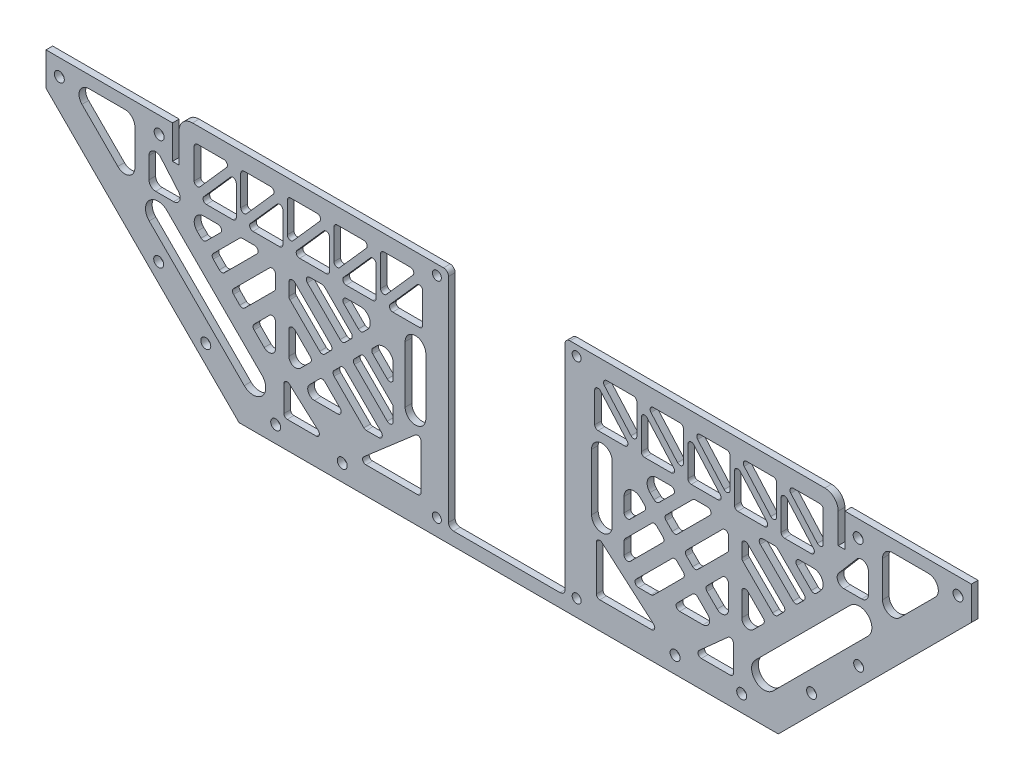
SolidWorks part; units mm, degrees
material "Thornel Mat VMA"
ref_plane "前视基准面" through (0, 0, 0) normal (0, 0, 1) x (1, 0, 0)
ref_plane "上视基准面" through (0, 0, 0) normal (0, 1, 0) x (1, 0, 0)
ref_plane "右视基准面" through (0, 0, 0) normal (1, 0, 0) x (0, 0, -1)
sketch "草图1" plane through (0, 0, 0) normal (0, 0, 1) x (1, 0, 0)
  line L0 (-101, 30) -> (-101, 0)
  line L1 (-101, 0) -> (101, 0)
  line L2 (101, 0) -> (101, 30)
  line L3 (-101, 30) -> (-139, 30)
  line L5 (-81, -58) -> (81, -58)
  line L7 (139, 30) -> (101, 30)
  line L8 (0, 0) -> (0, -58) construction
  line L9 (-135, 25) -> (-105, 25) construction
  line L10 (-135, 25) -> (-135, 5) construction
  line L11 (-135, 5) -> (-105, 5) construction
  line L12 (-105, 25) -> (-105, 5) construction
  line L13 (105, 25) -> (105, 5) construction
  line L14 (135, 5) -> (105, 5) construction
  line L15 (135, 25) -> (135, 5) construction
  line L16 (135, 25) -> (105, 25) construction
  line L17 (-70, -53) -> (-50, -53) construction
  line L18 (70, -53) -> (50, -53) construction
  line L19 (-139, 30) -> (-139, 0)
  line L20 (-139, 0) -> (-81, -58)
  line L21 (81, -58) -> (139, 0)
  line L22 (139, 0) -> (139, 30)
  circle A0 centre (-135, 25) radius 1.5
  circle A1 centre (-105, 25) radius 1.5
  circle A2 centre (-105, 5) radius 1.5
  circle A3 centre (-135, 5) radius 1.5
  circle A4 centre (135, 5) radius 1.5
  circle A5 centre (105, 5) radius 1.5
  circle A6 centre (105, 25) radius 1.5
  circle A7 centre (135, 25) radius 1.5
  circle A8 centre (-70, -53) radius 1.5
  circle A9 centre (-50, -53) radius 1.5
  circle A10 centre (50, -53) radius 1.5
  circle A11 centre (70, -53) radius 1.5
  point P4 (0, 0)
  dimension "D5" = 3
  dimension "D10" = 3
  dimension "D1" = 30
  dimension "D2" = 202
  dimension "D3" = 58
  dimension "D4" = 38
  dimension "D6" = 5
  dimension "D7" = 5
  dimension "D8" = 4
  dimension "D9" = 4
  dimension "D11" = 20
  dimension "D12" = 50
  dimension "D13" = 5
  dimension "D14" = 45
extrude "凸台-拉伸1" add sketch "草图1" along normal blind 2
sketch "草图2" plane through (0, 0, 2) normal (0, 0, 1) x (1, 0, 0)
  line L0 (-105.1421, -28.201) -> (-91, -42.3431) construction
  line L1 (0, 0) -> (0, -58) construction
  line L2 (-81, -58) -> (81, -58) construction
  line L3 (-139, 0) -> (-81, -58) construction
  line L4 (105.1421, -28.201) -> (91, -42.3431) construction
  circle A0 centre (-105.1421, -28.201) radius 1.5
  circle A1 centre (-91, -42.3431) radius 1.5
  circle A2 centre (91, -42.3431) radius 1.5
  circle A3 centre (105.1421, -28.201) radius 1.5
  dimension "D3" = 3
  dimension "D1" = 4
  dimension "D2" = 20
  dimension "D4" = 10
extrude "切除-拉伸1" cut sketch "草图2" against normal through all
sketch "草图3" plane through (0, 0, 2) normal (0, 0, 1) x (1, 0, 0)
  line L0 (139, 0) -> (139, 30) construction
  line L1 (-139, 30) -> (139, 30)
  line L2 (-139, 30) -> (-139, 10)
  line L3 (-139, 10) -> (139, 10)
  line L4 (139, 30) -> (139, 10)
  circle A0 centre (135, 5) radius 1.5 construction
  dimension "D1" = 5
extrude "切除-拉伸2" cut sketch "草图3" against normal through all
sketch "草图4" plane through (0, 0, 2) normal (0, 0, 1) x (1, 0, 0)
  line L0 (0, 0) -> (0, -58) construction
  line L1 (-81, -58) -> (81, -58) construction
  line L2 (-99, 0) -> (-99, 9)
  line L3 (101, 0) -> (-101, 0) construction
  line L4 (-95, 13) -> (95, 13)
  line L5 (0, 13) -> (0, 0)
  line L6 (-101, 0) -> (-101, 10) construction
  line L7 (-99, 0) -> (99, 0)
  line L8 (99, 0) -> (99, 9)
  arc A0 (-95, 13) -> (-99, 9) centre (-95, 9) ccw
  arc A1 (95, 13) -> (99, 9) centre (95, 9) cw
  line M15 (101, 0) -> (-101, 0)
  dimension "D3" = 4
  dimension "D1" = 2
  dimension "D2" = 13
extrude "凸台-拉伸2" add sketch "草图4" against normal up to surface (2 mm away) contours L4 A0 L2 L5 M15 | A1 L4 L5 L8 M15 up to face at (-103.6421, -28.201, 0)
sketch "草图8" plane through (0, 0, 2) normal (0, 0, 1) x (1, 0, 0)
  line L0 (-18.0726, -54) -> (16.9274, -54)
  line L1 (16.9274, -54) -> (16.9274, 16.3442)
  line L2 (16.9274, 16.3442) -> (-18.0726, 16.3442)
  line L3 (-18.0726, 16.3442) -> (-18.0726, -54)
  line L4 (-81, -58) -> (81, -58) construction
  line L48 (14.9274, 12.8) -> (14.9274, -43)
  line L49 (14.9274, -43) -> (13.9274, -43)
  line L50 (13.9274, -43) -> (13.9274, -31)
  line L51 (13.9274, -31) -> (11.9274, -31)
  line L52 (11.9274, -31) -> (11.9274, -43)
  line L53 (11.9274, -43) -> (10.9274, -43)
  line L54 (10.9274, -43) -> (10.9274, -31)
  line L55 (10.9274, -31) -> (8.9274, -31)
  line L56 (8.9274, -31) -> (8.9274, -43)
  line L57 (8.9274, -43) -> (7.9274, -43)
  line L58 (7.9274, -43) -> (7.9274, 12.8)
  line L59 (7.9274, 12.8) -> (5.9274, 12.8)
  line L60 (5.9274, 12.8) -> (5.9274, -43)
  line L61 (5.9274, -43) -> (4.9274, -43)
  line L62 (4.9274, -43) -> (4.9274, 12.8)
  line L63 (4.9274, 12.8) -> (2.9274, 12.8)
  line L64 (2.9274, 12.8) -> (2.9274, -43)
  line L65 (2.9274, -43) -> (1.9274, -43)
  line L66 (1.9274, -43) -> (1.9274, 12.8)
  line L67 (1.9274, 12.8) -> (-0.0726, 12.8)
  line L68 (-0.0726, 12.8) -> (-0.0726, -43)
  line L69 (-0.0726, -43) -> (-1.0726, -43)
  line L70 (-1.0726, -43) -> (-1.0726, 12.8)
  line L71 (-1.0726, 12.8) -> (-3.0726, 12.8)
  line L72 (-3.0726, 12.8) -> (-3.0726, -43)
  line L73 (-3.0726, -43) -> (-4.0726, -43)
  line L74 (-4.0726, -43) -> (-4.0726, 12.8)
  line L75 (-4.0726, 12.8) -> (-6.0726, 12.8)
  line L76 (-6.0726, 12.8) -> (-6.0726, -43)
  line L77 (-6.0726, -43) -> (-7.0726, -43)
  line L78 (-7.0726, -43) -> (-7.0726, 12.8)
  line L79 (-7.0726, 12.8) -> (-9.0726, 12.8)
  line L80 (-9.0726, 12.8) -> (-9.0726, -43)
  line L81 (-9.0726, -43) -> (-10.0726, -43)
  line L82 (-10.0726, -43) -> (-10.0726, 12.8)
  line L83 (-10.0726, 12.8) -> (-12.0726, 12.8)
  line L84 (-12.0726, 12.8) -> (-12.0726, -43)
  line L85 (-12.0726, -43) -> (-13.0726, -43)
  line L86 (-13.0726, -43) -> (-13.0726, 12.8)
  line L87 (-13.0726, 12.8) -> (-15.0726, 12.8)
  line L88 (-15.0726, 12.8) -> (-15.0726, -43)
  line L89 (-15.0726, -43) -> (-16.0726, -43)
  line L90 (-16.0726, -43) -> (-16.0726, 12.8)
  line L91 (-16.0726, 12.8) -> (-21.5726, 12.8)
  line L92 (-24.3726, 10) -> (-24.3726, -53)
  line L93 (-21.5726, -55.8) -> (20.4274, -55.8)
  line L94 (23.2274, -53) -> (23.2274, 10)
  line L95 (20.4274, 12.8) -> (14.9274, 12.8)
  line L96 (14.9274, 12.8) -> (14.9274, -43)
  line L97 (14.9274, -43) -> (13.9274, -43)
  line L98 (13.9274, -43) -> (13.9274, -31)
  line L99 (13.9274, -31) -> (11.9274, -31)
  line L100 (11.9274, -31) -> (11.9274, -43)
  line L101 (11.9274, -43) -> (10.9274, -43)
  line L102 (10.9274, -43) -> (10.9274, -31)
  line L103 (10.9274, -31) -> (8.9274, -31)
  line L104 (8.9274, -31) -> (8.9274, -43)
  line L105 (8.9274, -43) -> (7.9274, -43)
  line L106 (7.9274, -43) -> (7.9274, 12.8)
  line L107 (7.9274, 12.8) -> (5.9274, 12.8)
  line L108 (5.9274, 12.8) -> (5.9274, -43)
  line L109 (5.9274, -43) -> (4.9274, -43)
  line L110 (4.9274, -43) -> (4.9274, 12.8)
  line L111 (4.9274, 12.8) -> (2.9274, 12.8)
  line L112 (2.9274, 12.8) -> (2.9274, -43)
  line L113 (2.9274, -43) -> (1.9274, -43)
  line L114 (1.9274, -43) -> (1.9274, 12.8)
  line L115 (1.9274, 12.8) -> (-0.0726, 12.8)
  line L116 (-0.0726, 12.8) -> (-0.0726, -43)
  line L117 (-0.0726, -43) -> (-1.0726, -43)
  line L118 (-1.0726, -43) -> (-1.0726, 12.8)
  line L119 (-1.0726, 12.8) -> (-3.0726, 12.8)
  line L120 (-3.0726, 12.8) -> (-3.0726, -43)
  line L121 (-3.0726, -43) -> (-4.0726, -43)
  line L122 (-4.0726, -43) -> (-4.0726, 12.8)
  line L123 (-4.0726, 12.8) -> (-6.0726, 12.8)
  line L124 (-6.0726, 12.8) -> (-6.0726, -43)
  line L125 (-6.0726, -43) -> (-7.0726, -43)
  line L126 (-7.0726, -43) -> (-7.0726, 12.8)
  line L127 (-7.0726, 12.8) -> (-9.0726, 12.8)
  line L128 (-9.0726, 12.8) -> (-9.0726, -43)
  line L129 (-9.0726, -43) -> (-10.0726, -43)
  line L130 (-10.0726, -43) -> (-10.0726, 12.8)
  line L131 (-10.0726, 12.8) -> (-12.0726, 12.8)
  line L132 (-12.0726, 12.8) -> (-12.0726, -43)
  line L133 (-12.0726, -43) -> (-13.0726, -43)
  line L134 (-13.0726, -43) -> (-13.0726, 12.8)
  line L135 (-13.0726, 12.8) -> (-15.0726, 12.8)
  line L136 (-15.0726, 12.8) -> (-15.0726, -43)
  line L137 (-15.0726, -43) -> (-16.0726, -43)
  line L138 (-16.0726, -43) -> (-16.0726, 12.8)
  line L139 (-16.0726, 12.8) -> (-21.5726, 12.8)
  line L140 (-24.3726, 10) -> (-24.3726, -53)
  line L141 (-21.5726, -55.8) -> (20.4274, -55.8)
  line L142 (23.2274, -53) -> (23.2274, 10)
  line L143 (20.4274, 12.8) -> (14.9274, 12.8)
  circle A0 centre (20.4274, 10) radius 1.35 construction
  circle A1 centre (-21.5726, 10) radius 1.35 construction
  circle A2 centre (-21.5726, -53) radius 1.35 construction
  circle A3 centre (20.4274, -53) radius 1.35 construction
  arc A4 (-21.5726, 12.8) -> (-24.3726, 10) centre (-21.5726, 10) ccw
  arc A5 (-24.3726, -53) -> (-21.5726, -55.8) centre (-21.5726, -53) ccw
  arc A6 (20.4274, -55.8) -> (23.2274, -53) centre (20.4274, -53) ccw
  arc A7 (23.2274, 10) -> (20.4274, 12.8) centre (20.4274, 10) ccw
  arc A8 (-21.5726, 12.8) -> (-24.3726, 10) centre (-21.5726, 10) ccw
  arc A9 (-24.3726, -53) -> (-21.5726, -55.8) centre (-21.5726, -53) ccw
  arc A10 (20.4274, -55.8) -> (23.2274, -53) centre (20.4274, -53) ccw
  arc A11 (23.2274, 10) -> (20.4274, 12.8) centre (20.4274, 10) ccw
  circle A12 centre (20.4274, 10) radius 1.35
  circle A13 centre (-21.5726, 10) radius 1.35
  circle A14 centre (-21.5726, -53) radius 1.35
  circle A15 centre (20.4274, -53) radius 1.35
  line M64 (95, 13) -> (-95, 13)
  dimension "D2" = 2
  dimension "D3" = 2
  dimension "D4" = 4
  dimension "D1" = 0
extrude "切除-拉伸6" cut sketch "草图8" against normal blind 10 contours L1 L143 L96 L97 L98 L99 L100 L101 L102 L103 L104 L105 L106 L107 L108 L109 L110 L111 L112 L113 L114 L115 L116 L117 L118 L119 L120 L121 L122 L123 L124 L125 L126 L127 L128 L129 L130 L131 L132 L133 L134 L135 L136 L137 L138 L139 L3 L0 | L143 L1 L3 L139 L138 L137 L136 L135 L134 L133 L132 L131 L130 L129 L128 L127 L126 L125 L124 L123 L122 L121 L120 L119 L118 L117 L116 L115 L114 L113 L112 L111 L110 L109 L108 L107 L106 L105 L104 L103 L102 L101 L100 L99 L98 L97 L96 M64 | L2 L3 L1 M64 | A14 | A15 | A12 | A13
fillet "圆角2" radius 1.5 4 edges at (16.9274, 13, 1) (-18.0726, 13, 1) (16.9274, -54, 1) (-18.0726, -54, 1)
sketch "草图9" plane through (0, 0, 2) normal (0, 0, 1) x (1, 0, 0)
  line L0 (-105.327, -16.3413) -> (-76.7637, -44.9046) construction
  line L3 (-102.6508, -13.6651) -> (-74.0875, -42.2284)
  line L6 (-108.0031, -19.0174) -> (-79.4398, -47.5807)
  line L9 (-139, 0) -> (-81, -58) construction
  line L10 (-80.0246, -9.5495) -> (-76.3296, -9.5495)
  line L11 (-126.0803, 6.3467) -> (-115.3054, 6.3467)
  line L12 (-112.3054, 3.3467) -> (-112.3054, -7.4282)
  line L13 (-117.4268, -9.5495) -> (-128.2017, 1.2254)
  line L14 (-104.5409, -0.7265) -> (-99.1595, -7.0389)
  line L15 (-100.6815, -10.3364) -> (-106.0629, -10.3364)
  line L16 (-108.0629, -8.3364) -> (-108.0629, -2.024)
  line L17 (-91.583, -9.5495) -> (-87.3282, -9.5495)
  line L18 (-70.033, -13.8917) -> (-70.033, -17.6295)
  line L19 (-73.4472, -34.6588) -> (-76.4836, -31.6224)
  line L20 (-80.7738, -9.8598) -> (-88.7608, -17.8469)
  line L21 (-75.5804, -11.3582) -> (-85.4149, -21.1927)
  line L22 (-71.8417, -13.1425) -> (-82.6535, -23.9542)
  line L23 (-86.579, -11.3582) -> (-90.9142, -15.6935)
  line L24 (-70.3434, -18.3787) -> (-79.2862, -27.3215)
  line L25 (-86.9133, -21.1927) -> (-88.7608, -19.3452)
  line L26 (-80.7846, -27.3215) -> (-82.6535, -25.4526)
  line L27 (-70.033, -26.2313) -> (-70.033, -33.2446)
  line L28 (0, -58) -> (0, 0) construction
  line L29 (-71.8417, -25.4821) -> (-76.4836, -30.1241)
  line L30 (-92.4126, -15.6935) -> (-93.6255, -14.4805)
  line L31 (-81, -58) -> (81, -58) construction
  line L32 (-18.0726, -20.5) -> (0, -20.5) construction
  line L33 (-18.0726, 11.5) -> (-18.0726, -52.5) construction
  line L44 (-48.229, -20.269) -> (-46.8148, -21.6832) construction
  line L49 (-70.033, -15.7606) -> (-68.033, -15.7606) construction
  line L50 (-68.033, -15.7606) -> (-68.033, -17.2319) construction
  line L51 (-43.6535, -15.6935) -> (-42.4405, -14.4805)
  line L52 (-49.4871, -11.3582) -> (-45.1518, -15.6935)
  line L53 (-44.483, -9.5495) -> (-48.7379, -9.5495)
  line L54 (-56.0414, -9.5495) -> (-59.7365, -9.5495)
  line L55 (-60.4856, -11.3582) -> (-50.6511, -21.1927)
  line L56 (-49.1527, -21.1927) -> (-47.3052, -19.3452)
  line L57 (-55.2922, -9.8598) -> (-47.3052, -17.8469)
  line L58 (-66.033, -13.8917) -> (-66.033, -17.6295)
  line L59 (-65.7227, -18.3787) -> (-56.7799, -27.3215)
  line L60 (-55.2815, -27.3215) -> (-53.4126, -25.4526)
  line L61 (-64.2243, -13.1425) -> (-53.4126, -23.9542)
  line L62 (-66.033, -26.2313) -> (-66.033, -33.2446)
  line L63 (-64.2243, -25.4821) -> (-59.5824, -30.1241)
  line L64 (-62.6188, -34.6588) -> (-59.5824, -31.6224)
  line L65 (-46.8148, -21.6832) -> (-45.4006, -20.269) construction
  line L66 (-34.6811, -19.3514) -> (-34.6811, -23.6063)
  line L67 (-36.4898, -24.3555) -> (-40.825, -20.0203)
  line L68 (-40.825, -18.5219) -> (-39.6121, -17.309)
  line L69 (-34.9914, -30.1607) -> (-42.9784, -22.1737)
  line L70 (-46.3243, -24.0212) -> (-44.4768, -22.1737)
  line L71 (-36.4898, -35.3541) -> (-46.3243, -25.5195)
  line L72 (-34.6811, -30.9099) -> (-34.6811, -34.6049)
  line L73 (-38.274, -39.0928) -> (-49.0858, -28.281)
  line L74 (-52.4531, -30.1499) -> (-50.5842, -28.281)
  line L75 (-43.5102, -40.5911) -> (-52.4531, -31.6483)
  line L76 (-39.0232, -40.9015) -> (-42.7611, -40.9015)
  line L77 (-51.3629, -40.9015) -> (-58.3762, -40.9015)
  line L78 (-50.6137, -39.0928) -> (-55.2556, -34.4509)
  line L79 (-59.7904, -37.4873) -> (-56.754, -34.4509)
  line L80 (-65.8616, -40.396) -> (-57.2022, -48.1573)
  line L81 (-57.8696, -49.9019) -> (-66.529, -49.9019)
  line L82 (-67.529, -48.9019) -> (-67.529, -41.1406)
  line L83 (-28.002, -34.6782) -> (-43.5483, -48.1461)
  line L84 (-42.8936, -49.9019) -> (-27.3472, -49.9019)
  line L85 (-26.3472, -48.9019) -> (-26.3472, -35.434)
  line L86 (-28.002, -11.9698) -> (-28.002, -29.0302) construction
  line L87 (-24.8989, -11.9698) -> (-24.8989, -29.0302)
  line L88 (-31.105, -11.9698) -> (-31.105, -29.0302)
  line L100 (-94.4948, 7.1872) -> (-94.4948, -1.8511)
  line L102 (-85.5038, 8.1872) -> (-93.4948, 8.1872)
  line L103 (-90.831, -6.1261) -> (-82.8401, -6.1261)
  line L104 (-81.8401, -5.1261) -> (-81.8401, 3.9122)
  line L105 (-80.4948, 7.1872) -> (-80.4948, -1.8511)
  line L106 (-84.7546, 6.5248) -> (-92.7456, -2.5135)
  line L107 (-83.5893, 4.5745) -> (-91.5802, -4.4637)
  line L108 (-70.7546, 6.5248) -> (-78.7456, -2.5135)
  line L109 (-71.5038, 8.1872) -> (-79.4948, 8.1872)
  line L110 (-76.831, -6.1261) -> (-68.8401, -6.1261)
  line L111 (-67.8401, -5.1261) -> (-67.8401, 3.9122)
  line L112 (-69.5893, 4.5745) -> (-77.5802, -4.4637)
  line L113 (-66.4948, 7.1872) -> (-66.4948, -1.8511)
  line L114 (-56.7546, 6.5248) -> (-64.7456, -2.5135)
  line L115 (-57.5038, 8.1872) -> (-65.4948, 8.1872)
  line L116 (-62.831, -6.1261) -> (-54.8401, -6.1261)
  line L117 (-53.8401, -5.1261) -> (-53.8401, 3.9122)
  line L118 (-55.5893, 4.5745) -> (-63.5802, -4.4637)
  line L119 (-52.4948, 7.1872) -> (-52.4948, -1.8511)
  line L120 (-42.7546, 6.5248) -> (-50.7456, -2.5135)
  line L121 (-43.5038, 8.1872) -> (-51.4948, 8.1872)
  line L122 (-48.831, -6.1261) -> (-40.8401, -6.1261)
  line L123 (-39.8401, -5.1261) -> (-39.8401, 3.9122)
  line L124 (-41.5893, 4.5745) -> (-49.5802, -4.4637)
  line L125 (-38.4948, 7.1872) -> (-38.4948, -1.8511)
  line L126 (-28.7546, 6.5248) -> (-36.7456, -2.5135)
  line L127 (-29.5038, 8.1872) -> (-37.4948, 8.1872)
  line L128 (-34.831, -6.1261) -> (-26.8401, -6.1261)
  line L129 (-25.8401, -5.1261) -> (-25.8401, 3.9122)
  line L130 (-27.5893, 4.5745) -> (-35.5802, -4.4637)
  arc A6 (-102.6508, -13.6651) -> (-108.0031, -19.0174) centre (-105.327, -16.3413) ccw
  arc A7 (-79.4398, -47.5807) -> (-74.0875, -42.2284) centre (-76.7637, -44.9046) ccw
  arc A8 (-112.3054, -7.4282) -> (-117.4268, -9.5495) centre (-115.3054, -7.4282) cw
  arc A9 (-112.3054, 3.3467) -> (-115.3054, 6.3467) centre (-115.3054, 3.3467) ccw
  arc A10 (-126.0803, 6.3467) -> (-128.2017, 1.2254) centre (-126.0803, 3.3467) ccw
  arc A11 (-100.6815, -10.3364) -> (-99.1595, -7.0389) centre (-100.6815, -8.3364) ccw
  arc A12 (-106.0629, -10.3364) -> (-108.0629, -8.3364) centre (-106.0629, -8.3364) cw
  arc A13 (-104.5409, -0.7265) -> (-108.0629, -2.024) centre (-106.0629, -2.024) ccw
  arc A14 (-70.033, -33.2446) -> (-73.4472, -34.6588) centre (-72.033, -33.2446) cw
  arc A16 (-91.583, -9.5495) -> (-93.6255, -14.4805) centre (-91.583, -12.438) ccw
  arc A17 (-70.033, -26.2313) -> (-71.8417, -25.4821) centre (-71.0925, -26.2313) ccw
  arc A18 (-76.4836, -31.6224) -> (-76.4836, -30.1241) centre (-75.7344, -30.8732) cw
  arc A19 (-79.2862, -27.3215) -> (-80.7846, -27.3215) centre (-80.0354, -26.5723) cw
  arc A20 (-70.033, -17.6295) -> (-70.3434, -18.3787) centre (-71.0925, -17.6295) cw
  arc A21 (-70.033, -13.8917) -> (-71.8417, -13.1425) centre (-71.0925, -13.8917) ccw
  arc A22 (-82.6535, -25.4526) -> (-82.6535, -23.9542) centre (-81.9043, -24.7034) cw
  arc A23 (-75.5804, -11.3582) -> (-76.3296, -9.5495) centre (-76.3296, -10.609) ccw
  arc A24 (-85.4149, -21.1927) -> (-86.9133, -21.1927) centre (-86.1641, -20.4436) cw
  arc A25 (-88.7608, -19.3452) -> (-88.7608, -17.8469) centre (-88.0117, -18.596) cw
  arc A26 (-80.0246, -9.5495) -> (-80.7738, -9.8598) centre (-80.0246, -10.609) ccw
  arc A27 (-86.579, -11.3582) -> (-87.3282, -9.5495) centre (-87.3282, -10.609) ccw
  arc A28 (-90.9142, -15.6935) -> (-92.4126, -15.6935) centre (-91.6634, -14.9443) cw
  arc A35 (-44.483, -9.5495) -> (-42.4405, -14.4805) centre (-44.483, -12.438) cw
  arc A36 (-45.1518, -15.6935) -> (-43.6535, -15.6935) centre (-44.4026, -14.9443) ccw
  arc A37 (-49.4871, -11.3582) -> (-48.7379, -9.5495) centre (-48.7379, -10.609) cw
  arc A38 (-60.4856, -11.3582) -> (-59.7365, -9.5495) centre (-59.7365, -10.609) cw
  arc A39 (-50.6511, -21.1927) -> (-49.1527, -21.1927) centre (-49.9019, -20.4436) ccw
  arc A40 (-47.3052, -19.3452) -> (-47.3052, -17.8469) centre (-48.0544, -18.596) ccw
  arc A41 (-56.0414, -9.5495) -> (-55.2922, -9.8598) centre (-56.0414, -10.609) cw
  arc A42 (-66.033, -17.6295) -> (-65.7227, -18.3787) centre (-64.9735, -17.6295) ccw
  arc A43 (-56.7799, -27.3215) -> (-55.2815, -27.3215) centre (-56.0307, -26.5723) ccw
  arc A44 (-66.033, -13.8917) -> (-64.2243, -13.1425) centre (-64.9735, -13.8917) cw
  arc A45 (-53.4126, -25.4526) -> (-53.4126, -23.9542) centre (-54.1618, -24.7034) ccw
  arc A46 (-66.033, -33.2446) -> (-62.6188, -34.6588) centre (-64.033, -33.2446) ccw
  arc A47 (-66.033, -26.2313) -> (-64.2243, -25.4821) centre (-64.9735, -26.2313) cw
  arc A48 (-59.5824, -31.6224) -> (-59.5824, -30.1241) centre (-60.3316, -30.8732) ccw
  arc A49 (-36.4898, -24.3555) -> (-34.6811, -23.6063) centre (-35.7406, -23.6063) ccw
  arc A50 (-40.825, -20.0203) -> (-40.825, -18.5219) centre (-40.0758, -19.2711) cw
  arc A51 (-34.6811, -19.3514) -> (-39.6121, -17.309) centre (-37.5696, -19.3514) ccw
  arc A52 (-34.6811, -30.9099) -> (-34.9914, -30.1607) centre (-35.7406, -30.9099) ccw
  arc A53 (-44.4768, -22.1737) -> (-42.9784, -22.1737) centre (-43.7276, -22.9228) cw
  arc A54 (-46.3243, -25.5195) -> (-46.3243, -24.0212) centre (-45.5751, -24.7704) cw
  arc A55 (-36.4898, -35.3541) -> (-34.6811, -34.6049) centre (-35.7406, -34.6049) ccw
  arc A56 (-39.0232, -40.9015) -> (-38.274, -39.0928) centre (-39.0232, -39.842) ccw
  arc A57 (-50.5842, -28.281) -> (-49.0858, -28.281) centre (-49.835, -29.0302) cw
  arc A58 (-52.4531, -31.6483) -> (-52.4531, -30.1499) centre (-51.7039, -30.8991) cw
  arc A59 (-42.7611, -40.9015) -> (-43.5102, -40.5911) centre (-42.7611, -39.842) cw
  arc A60 (-51.3629, -40.9015) -> (-50.6137, -39.0928) centre (-51.3629, -39.842) ccw
  arc A61 (-56.754, -34.4509) -> (-55.2556, -34.4509) centre (-56.0048, -35.2) cw
  arc A62 (-58.3762, -40.9015) -> (-59.7904, -37.4873) centre (-58.3762, -38.9015) cw
  arc A63 (-57.2022, -48.1573) -> (-57.8696, -49.9019) centre (-57.8696, -48.9019) cw
  arc A64 (-66.529, -49.9019) -> (-67.529, -48.9019) centre (-66.529, -48.9019) cw
  arc A65 (-65.8616, -40.396) -> (-67.529, -41.1406) centre (-66.529, -41.1406) ccw
  arc A66 (-26.3472, -48.9019) -> (-27.3472, -49.9019) centre (-27.3472, -48.9019) cw
  arc A67 (-26.3472, -35.434) -> (-28.002, -34.6782) centre (-27.3472, -35.434) ccw
  arc A68 (-42.8936, -49.9019) -> (-43.5483, -48.1461) centre (-42.8936, -48.9019) cw
  arc A69 (-24.8989, -11.9698) -> (-31.105, -11.9698) centre (-28.002, -11.9698) ccw
  arc A70 (-31.105, -29.0302) -> (-24.8989, -29.0302) centre (-28.002, -29.0302) ccw
  arc A82 (-81.8401, -5.1261) -> (-82.8401, -6.1261) centre (-82.8401, -5.1261) cw
  arc A83 (-90.831, -6.1261) -> (-91.5802, -4.4637) centre (-90.831, -5.1261) cw
  arc A84 (-81.8401, 3.9122) -> (-83.5893, 4.5745) centre (-82.8401, 3.9122) ccw
  arc A85 (-84.7546, 6.5248) -> (-85.5038, 8.1872) centre (-85.5038, 7.1872) ccw
  arc A86 (-93.4948, 8.1872) -> (-94.4948, 7.1872) centre (-93.4948, 7.1872) ccw
  arc A87 (-92.7456, -2.5135) -> (-94.4948, -1.8511) centre (-93.4948, -1.8511) cw
  arc A88 (-78.7456, -2.5135) -> (-80.4948, -1.8511) centre (-79.4948, -1.8511) cw
  arc A89 (-79.4948, 8.1872) -> (-80.4948, 7.1872) centre (-79.4948, 7.1872) ccw
  arc A90 (-70.7546, 6.5248) -> (-71.5038, 8.1872) centre (-71.5038, 7.1872) ccw
  arc A91 (-76.831, -6.1261) -> (-77.5802, -4.4637) centre (-76.831, -5.1261) cw
  arc A92 (-67.8401, -5.1261) -> (-68.8401, -6.1261) centre (-68.8401, -5.1261) cw
  arc A93 (-67.8401, 3.9122) -> (-69.5893, 4.5745) centre (-68.8401, 3.9122) ccw
  arc A94 (-64.7456, -2.5135) -> (-66.4948, -1.8511) centre (-65.4948, -1.8511) cw
  arc A95 (-65.4948, 8.1872) -> (-66.4948, 7.1872) centre (-65.4948, 7.1872) ccw
  arc A96 (-56.7546, 6.5248) -> (-57.5038, 8.1872) centre (-57.5038, 7.1872) ccw
  arc A97 (-62.831, -6.1261) -> (-63.5802, -4.4637) centre (-62.831, -5.1261) cw
  arc A98 (-53.8401, -5.1261) -> (-54.8401, -6.1261) centre (-54.8401, -5.1261) cw
  arc A99 (-53.8401, 3.9122) -> (-55.5893, 4.5745) centre (-54.8401, 3.9122) ccw
  arc A100 (-50.7456, -2.5135) -> (-52.4948, -1.8511) centre (-51.4948, -1.8511) cw
  arc A101 (-51.4948, 8.1872) -> (-52.4948, 7.1872) centre (-51.4948, 7.1872) ccw
  arc A102 (-42.7546, 6.5248) -> (-43.5038, 8.1872) centre (-43.5038, 7.1872) ccw
  arc A103 (-48.831, -6.1261) -> (-49.5802, -4.4637) centre (-48.831, -5.1261) cw
  arc A104 (-39.8401, -5.1261) -> (-40.8401, -6.1261) centre (-40.8401, -5.1261) cw
  arc A105 (-39.8401, 3.9122) -> (-41.5893, 4.5745) centre (-40.8401, 3.9122) ccw
  arc A106 (-36.7456, -2.5135) -> (-38.4948, -1.8511) centre (-37.4948, -1.8511) cw
  arc A107 (-37.4948, 8.1872) -> (-38.4948, 7.1872) centre (-37.4948, 7.1872) ccw
  arc A108 (-28.7546, 6.5248) -> (-29.5038, 8.1872) centre (-29.5038, 7.1872) ccw
  arc A109 (-34.831, -6.1261) -> (-35.5802, -4.4637) centre (-34.831, -5.1261) cw
  arc A110 (-25.8401, -5.1261) -> (-26.8401, -6.1261) centre (-26.8401, -5.1261) cw
  arc A111 (-25.8401, 3.9122) -> (-27.5893, 4.5745) centre (-26.8401, 3.9122) ccw
  point P2 (-91.0453, -30.6229)
  point P33 (-70.033, -23.6735)
  point P52 (-80.0354, -28.0707)
  point P61 (-73.7717, -9.5495)
  point P64 (-86.1641, -21.9419)
  point P69 (-80.4635, -9.5495)
  point P74 (-91.6634, -16.4427)
  point P186 (-28.002, -20.5)
  dimension "D1" = 3
  dimension "D2" = 2
  dimension "D3" = 2
  dimension "D4" = 1.0595
  dimension "D5" = 2
  dimension "D7" = 1
  dimension "D8" = 1
  dimension "D9" = 1
  dimension "D6" = 2
  dimension "D10" = 5
extrude "切除-拉伸7" cut sketch "草图9" against normal blind 10
mirror "镜向1" about plane through (0, 0, 0) normal (1, 0, 0) of "切除-拉伸7"
